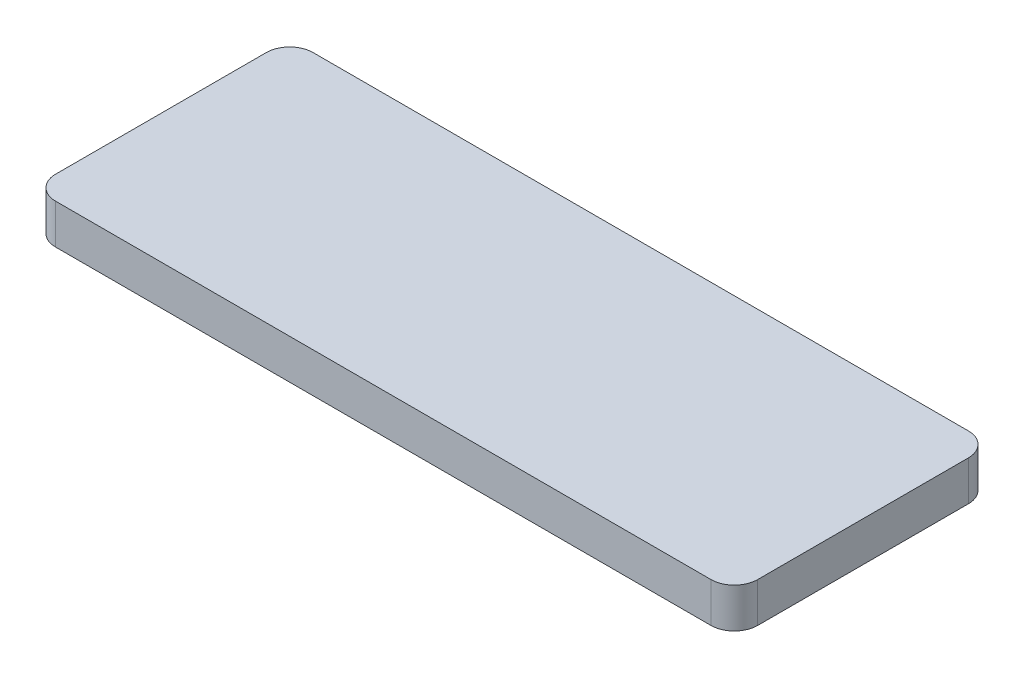
SolidWorks part; units mm, degrees
ref_plane "Front Plane" through (0, 0, 0) normal (0, 0, 1) x (1, 0, 0)
ref_plane "Top Plane" through (0, 0, 0) normal (0, 1, 0) x (1, 0, 0)
ref_plane "Right Plane" through (0, 0, 0) normal (1, 0, 0) x (0, 0, -1)
sketch "Sketch1" plane through (0, 0, 0) normal (0, 1, 0) x (1, 0, 0)
  line L1 (-70, -27.5) -> (70, -27.5)
  line L2 (-75, -22.5) -> (-75, 22.5)
  line L3 (-70, 27.5) -> (70, 27.5)
  line L4 (75, -22.5) -> (75, 22.5)
  line L5 (-75, -27.5) -> (75, 27.5) construction
  line L6 (-75, 27.5) -> (75, -27.5) construction
  arc A0 (-70, -27.5) -> (-75, -22.5) centre (-70, -22.5) cw
  arc A1 (70, -27.5) -> (75, -22.5) centre (70, -22.5) ccw
  arc A2 (70, 27.5) -> (75, 22.5) centre (70, 22.5) cw
  arc A3 (-75, 22.5) -> (-70, 27.5) centre (-70, 22.5) cw
  point P0 (0, 0)
  dimension "D3" = 5
  dimension "D1" = 150
  dimension "D2" = 55
extrude "Boss-Extrude1" add sketch "Sketch1" along normal blind 8.5
